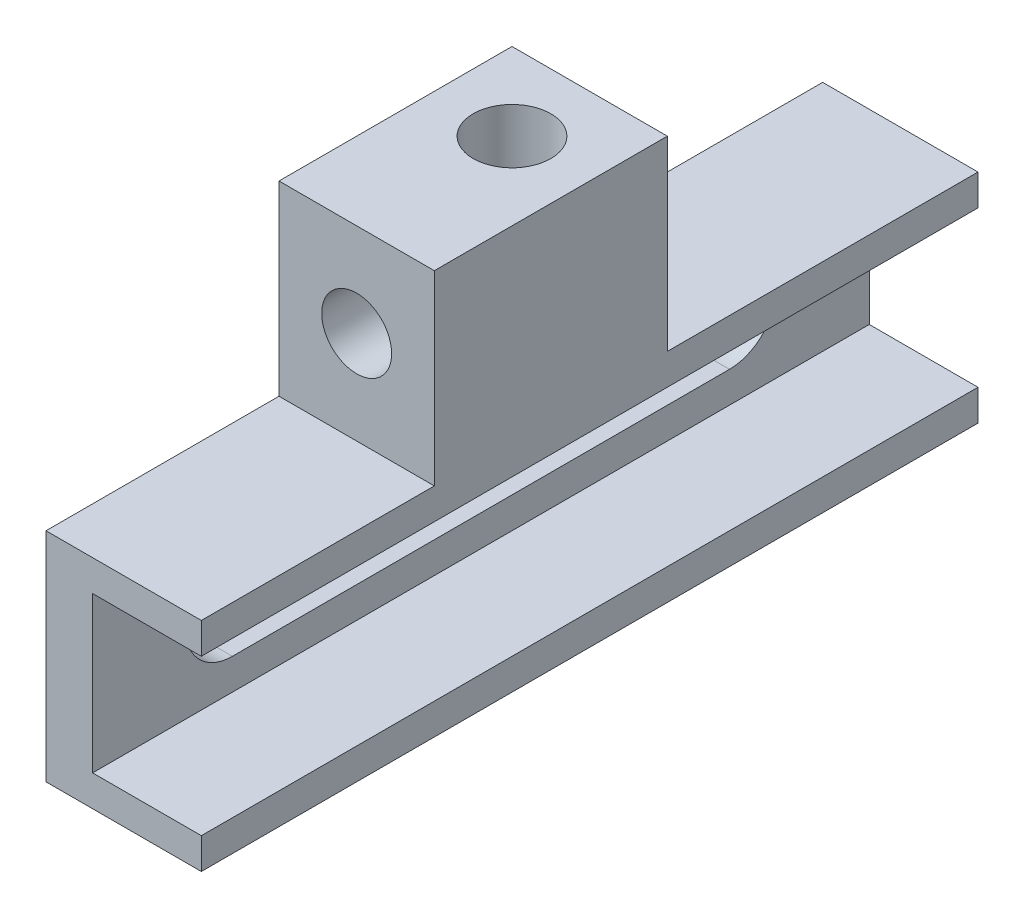
SolidWorks part; units mm, degrees
ref_plane "Front Plane" through (0, 0, 0) normal (0, 0, 1) x (1, 0, 0)
ref_plane "Top Plane" through (0, 0, 0) normal (0, 1, 0) x (1, 0, 0)
ref_plane "Right Plane" through (0, 0, 0) normal (1, 0, 0) x (0, 0, -1)
sketch "Sketch1" plane through (0, 0, 0) normal (0, 0, 1) x (1, 0, 0)
  line L0 (7.1963, -1) -> (-2, -1)
  line L1 (-5, -13) -> (5, -13)
  line L2 (-5, -13) -> (-5, 13)
  line L3 (-5, 13) -> (5, 13)
  line L4 (5, -13) -> (5, 13)
  line L5 (-5, -13) -> (5, 13) construction
  line L6 (-5, 13) -> (5, -13) construction
  line L7 (-2, -1) -> (-2, -11)
  line L8 (-2, -11) -> (7.1963, -11)
  line L9 (7.1963, -11) -> (7.1963, -1)
  point P0 (0, 0)
  dimension "D1" = 10
  dimension "D2" = 26
  dimension "D3" = 90
  dimension "D4" = 10
  dimension "D5" = 2
  dimension "D6" = 3
  dimension "D7" = 9.1963
extrude "Boss-Extrude1" add sketch "Sketch1" along normal blind 50 contours L8 L7 L0 L4 L3 L2 L1
sketch "Sketch2" plane through (5, 0, 0) normal (1, 0, 0) x (0, 0, -1)
  line L4 (-35, 13) -> (-50, 13)
  line L5 (-50, 1) -> (-35, 1)
  line L6 (-35, 1) -> (-20, 1)
  line L7 (-35, 1) -> (-35, 13)
  line L8 (-20, 1) -> (-20, 13)
  line L9 (-35, 13) -> (-20, 13)
  line L10 (-50, -1) -> (-50, 13) construction
  line L11 (-20, 1) -> (2.6682, 1)
  line L12 (-50, -1) -> (0, -1) construction
  line L13 (-35, 13) -> (-50, 13)
  line L14 (2.6682, 1) -> (3.1319, 15.0192)
  line L15 (3.1319, 15.0192) -> (-7.1213, 16.6679)
  line L16 (-7.1213, 16.6679) -> (-18.1909, 15.7245)
  line L17 (-18.1909, 15.7245) -> (-20, 13)
  line M5 (0, -1) -> (0, 13)
  line M6 (0, 13) -> (-50, 13)
  line M7 (-50, 13) -> (-50, -1)
  dimension "D1" = 15
  dimension "D2" = 12
  dimension "D3" = 15
  dimension "D4" = 2
extrude "Cut-Extrude1" cut sketch "Sketch2" against normal blind 50 contours L5 L7 M6 M7 | L8 L11 M5 M6
sketch "Sketch3" plane through (-2, 0, 0) normal (1, 0, 0) x (0, 0, -1)
  line L0 (-41, -6) -> (-9, -6) construction
  line L1 (-41, -3) -> (-9, -3)
  line L2 (-41, -9) -> (-9, -9)
  line L3 (-50, -1) -> (-50, -11) construction
  line L4 (-50, -11) -> (0, -11) construction
  arc A0 (-41, -3) -> (-41, -9) centre (-41, -6) ccw
  arc A1 (-9, -9) -> (-9, -3) centre (-9, -6) ccw
  point P2 (-25, -6)
  point P9 (-50, -6)
  point P12 (-25, -11)
  dimension "D3" = 32
  dimension "D1" = 6
  dimension "D2" = 0
  dimension "D4" = 0
extrude "Cut-Extrude2" cut sketch "Sketch3" against normal blind 50
hole_wizard "Ø5.0mm Dowel Hole1" positions "Sketch5" profile "Sketch6" hole size "Ø5.0" standard "ISO"
sketch "Sketch5" plane through (0, 13, 0) normal (0, 1, 0) x (1, 0, 0)
  line L0 (-5, -20) -> (5, -20) construction
  line L1 (-5, -35) -> (-5, -20) construction
  point P0 (0, -25)
  dimension "D1" = 5
  dimension "D2" = 5
sketch "Sketch6" plane through (0, 13, 25) normal (1, 0, 0) x (0, 0, 1)
  line L0 (0, 0) -> (0, 11.5022)
  line L1 (0, 11.5022) -> (2.5, 10)
  line L2 (2.5, 10) -> (2.5, 0)
  line L5 (2.5, 0) -> (0, 0)
  line L10 (0, 11.5022) -> (-2.5, 10) construction
  line L11 (0, -6.35) -> (0, 107.95) construction
  dimension "Hole Dia." = 5
  dimension "Hole Depth" = 10
  dimension "Drill Angle" = 118
sketch "Sketch7" plane through (0, 0, 35) normal (0, 0, 1) x (1, 0, 0)
  line L1 (-5, 13) -> (5, 13) construction
  circle A0 centre (0, 7) radius 2.25
  point P2 (0, 0)
  point P6 (0, 0)
  point P7 (0, 0)
  dimension "D1" = 4.5
  dimension "D2" = 6
extrude "Cut-Extrude3" cut sketch "Sketch7" against normal blind 10
ref_plane "Plane2" through (0, 0, 0) normal (1, 0, 0) x (0, 0, -1)
ref_plane "Plane3" through (0, -6, 0) normal (0, 1, 0) x (1, 0, 0)
